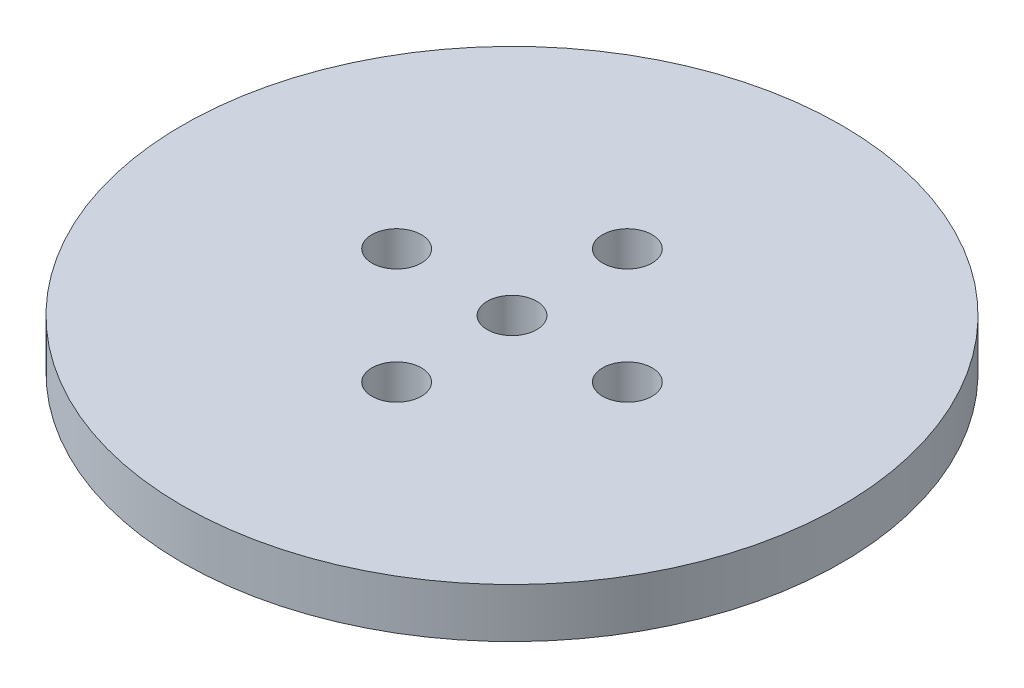
SolidWorks part; units mm, degrees
material "聚脂树脂"
ref_plane "前视基准面" through (0, 0, 0) normal (0, 0, 1) x (1, 0, 0)
ref_plane "上视基准面" through (0, 0, 0) normal (0, 1, 0) x (1, 0, 0)
ref_plane "右视基准面" through (0, 0, 0) normal (1, 0, 0) x (0, 0, -1)
other "Configuration Table"
sketch "草图1" plane through (0, 0, 0) normal (0, 1, 0) x (1, 0, 0)
  line L0 (0, 0) -> (0, 14) construction
  line L1 (0, 0) -> (14.0601, 0) construction
  circle A0 centre (0, 0) radius 20
  circle A1 centre (0, 7) radius 1.5
  circle A2 centre (0, 0) radius 1.5
  circle A3 centre (7, 0) radius 1.5
  circle A4 centre (-7, 0) radius 1.5
  circle A5 centre (0, -7) radius 1.5
  dimension "D1" = 3
  dimension "D2" = 3
  dimension "D3" = 3
  dimension "D4" = 7
  dimension "D5" = 7
  dimension "D6" = 40
extrude "凸台-拉伸1" add sketch "草图1" along normal blind 3
